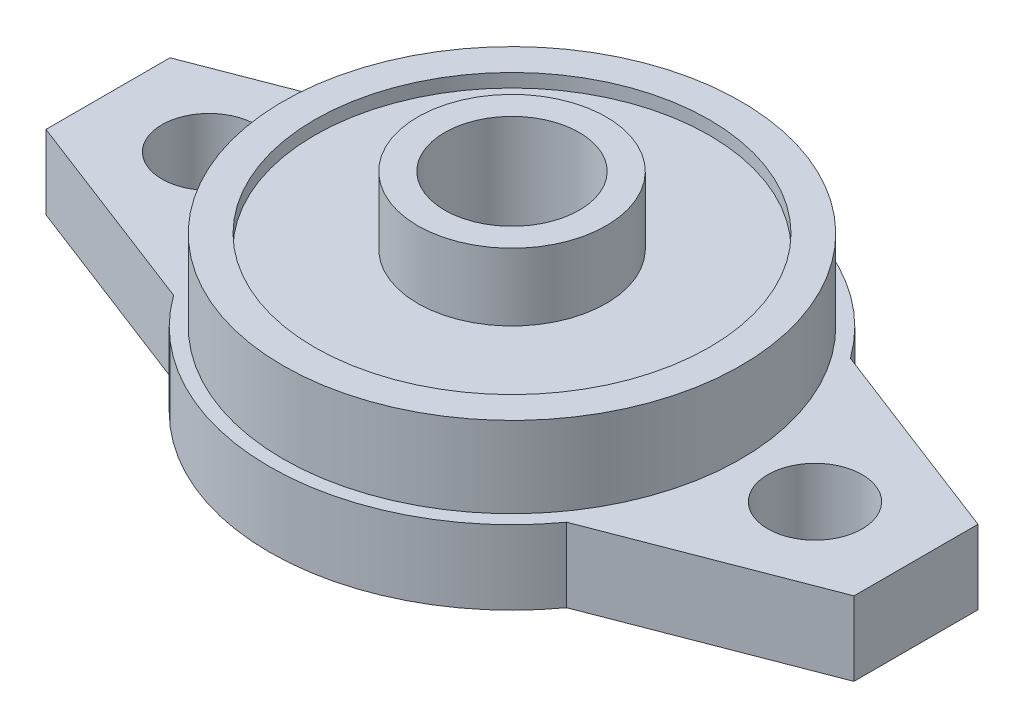
SolidWorks part; units mm, degrees
material "锌 AC41A 合金，作为铸件"
ref_plane "前视基准面" through (0, 0, 0) normal (0, 0, 1) x (1, 0, 0)
ref_plane "上视基准面" through (0, 0, 0) normal (0, 1, 0) x (1, 0, 0)
ref_plane "右视基准面" through (0, 0, 0) normal (1, 0, 0) x (0, 0, -1)
sketch "草图1" plane through (0, 0, 0) normal (0, 1, 0) x (1, 0, 0)
  line L0 (-643.3584, 0) -> (31524.5638, 0) construction
  line L1 (0, -643.3584) -> (0, 31524.5638) construction
  line L2 (-30, 4.605) -> (-30, -4.605)
  line L3 (-30, 4.605) -> (-14.5935, 10.5371)
  line L4 (-30, -4.605) -> (-14.5935, -10.5371)
  line L5 (30, -4.605) -> (14.5935, -10.5371)
  line L6 (30, 4.605) -> (14.5935, 10.5371)
  line L7 (30, 4.605) -> (30, -4.605)
  circle A0 centre (0, 0) radius 5
  circle A1 centre (0, 0) radius 18
  circle A2 centre (-22.5, 0) radius 3.5
  circle A3 centre (22.5, 0) radius 3.5
  point P13 (-30, 0)
  point P21 (30, 0)
  dimension "D1" = 7
  dimension "D2" = 36
  dimension "D3" = 10
  dimension "D4" = 30
  dimension "D5" = 22.5
extrude "凸台-拉伸1" add sketch "草图1" along normal blind 5.5 contours A1 L3 L2 L4 A2 | A1 A0 | A1 L5 L7 L6 A3
sketch "草图2" plane through (0, 5.5, 0) normal (0, 1, 0) x (1, 0, 0)
  circle A0 centre (0, 0) radius 17
  circle A1 centre (0, 0) radius 5 construction
  circle A2 centre (0, 0) radius 5
  dimension "D1" = 34
extrude "凸台-拉伸2" add sketch "草图2" along normal blind 6
sketch "草图3" plane through (0, 11.5, 0) normal (0, 1, 0) x (1, 0, 0)
  circle A0 centre (0, 0) radius 7
  circle A1 centre (0, 0) radius 5 construction
  circle A2 centre (0, 0) radius 5
  dimension "D1" = 14
extrude "凸台-拉伸3" add sketch "草图3" along normal blind 4
sketch "草图4" plane through (0, 11.5, 0) normal (0, 1, 0) x (1, 0, 0)
  circle A0 centre (0, 0) radius 7 construction
  circle A1 centre (0, 0) radius 7
  circle A2 centre (0, 0) radius 14.65
  circle A3 centre (0, 0) radius 17 construction
  dimension "D1" = 2.35
extrude "切除-拉伸1" cut sketch "草图4" against normal blind 1
